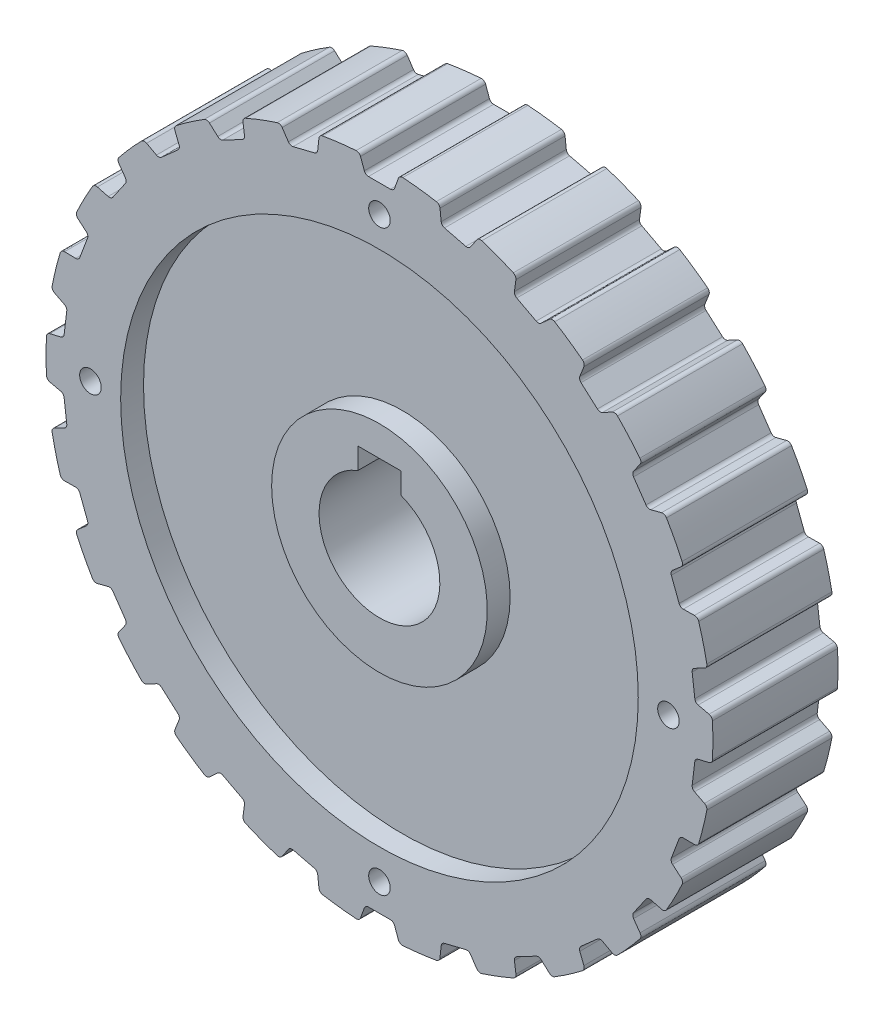
SolidWorks part; units mm, degrees
ref_plane "Front Plane" through (0, 0, 0) normal (0, 0, 1) x (1, 0, 0)
ref_plane "Top Plane" through (0, 0, 0) normal (0, 1, 0) x (1, 0, 0)
ref_plane "Right Plane" through (0, 0, 0) normal (1, 0, 0) x (0, 0, -1)
sketch "Sketch1" plane through (0, 0, 0) normal (0, 1, 0) x (1, 0, 0)
  line L0 (0, 36.1296) -> (0, -19.4741) construction
sketch "Sketch2" plane through (0, 0, 0) normal (0, 1, 0) x (1, 0, 0)
  line L0 (7, 7.25) -> (12.5, 7.25)
  line L1 (12.5, 7.25) -> (12.5, 4)
  line L2 (12.5, 4) -> (30, 4)
  line L3 (30, 4) -> (30, 7.25)
  line L4 (30, 7.25) -> (36, 7.25)
  line L5 (36, 7.25) -> (36, -7.25)
  line L6 (36, -7.25) -> (30, -7.25)
  line L7 (30, -7.25) -> (30, -4)
  line L8 (30, -4) -> (12.5, -4)
  line L9 (12.5, -4) -> (12.5, -7.25)
  line L10 (12.5, -7.25) -> (7, -7.25)
  line L11 (7, -7.25) -> (7, 7.25)
  line L12 (0, 0) -> (7, 0) construction
  line L13 (0, 200036.1296) -> (0, -200019.4741) construction
  dimension "D1" = 36
  dimension "D2" = 30
  dimension "D3" = 12.5
  dimension "D4" = 14.5
  dimension "D5" = 3.25
  dimension "D6" = 7
revolve "Revolve1" add sketch "Sketch2" angle 360 about L0
sketch "Sketch3" plane through (0, 0, 0) normal (0, 0, 1) x (1, 0, 0)
  line L0 (0, 0) -> (0, 9) construction
  line L1 (-2.5, 0) -> (2.5, 0)
  line L2 (-2.5, 0) -> (-2.5, 9)
  line L3 (-2.5, 9) -> (2.5, 9)
  line L4 (2.5, 0) -> (2.5, 9)
  line L5 (0, 9) -> (0, 12.5) construction
  circle A0 centre (0, 0) radius 12.5 construction
  dimension "D1" = 3.5
  dimension "D2" = 5
extrude "Cut-Extrude1" cut sketch "Sketch3" against normal through all both and the other way through all
sketch "Sketch4" plane through (0, 0, 0) normal (0, 0, 1) x (1, 0, 0)
  line L0 (0, 0) -> (0, 30) construction
  line L1 (0, 30) -> (0, 32) construction
  line L2 (0, 32) -> (0, 33.5) construction
  circle A0 centre (0, 0) radius 30 construction
  circle A1 centre (0, 33.5) radius 1.5 construction
  circle A2 centre (33.5, 0) radius 1.5 construction
  circle A3 centre (0, -33.5) radius 1.5 construction
  circle A4 centre (-33.5, 0) radius 1.5 construction
  point P18 (0, 0)
  dimension "D2" = 3
  dimension "D1" = 2
  dimension "D3" = 4
hole_wizard "M3x0.5 Tapped Hole1" positions "Sketch5" profile "Sketch6" tap size "M3x0.5" standard "ANSI Metric" end condition through all
sketch "Sketch5" plane through (0, 0, 7.25) normal (0, 0, 1) x (1, 0, 0)
  point P0 (0, 33.5)
  point P3 (33.5, 0)
  point P6 (-33.5, 0)
  point P9 (0, -33.5)
sketch "Sketch6" plane through (0, 33.5, 7.25) normal (1, 0, 0) x (0, -1, 0)
  line L0 (0, 0) -> (0, 14.5)
  line L1 (0, 14.5) -> (1.25, 14.5)
  line L2 (1.25, 14.5) -> (1.25, 0)
  line L5 (1.25, 0) -> (0, 0)
  line L11 (0, -6.35) -> (0, 107.95) construction
  dimension "Thru Tap Drill Dia." = 2.5
  dimension "Thru Tap Drill Depth" = 14.5
cosmetic thread "Hole Thread1" parameters "D2"=3
cosmetic thread "Hole Thread2" parameters "D2"=3
cosmetic thread "Hole Thread3" parameters "D2"=3
cosmetic thread "Hole Thread4" parameters "D2"=3
sketch "Sketch7" plane through (0, 0, 0) normal (0, 0, 1) x (1, 0, 0)
  line L0 (0, 0) -> (0, 37.6222) construction
  line L1 (-2.325, 38.5772) -> (-2.9401, 40.2672) construction
  line L2 (-2.325, 38.5772) -> (-1.6298, 36.6672) construction
  line L3 (-1.6298, 36.6672) -> (1.6298, 36.6672) construction
  line L4 (1.6298, 36.6672) -> (2.325, 38.5772) construction
  line L5 (2.325, 38.5772) -> (-2.325, 38.5772) construction
  line L6 (0, 36.6672) -> (0, 38.5772) construction
  line L7 (-2.9401, 40.2672) -> (2.9401, 40.2672) construction
  line L8 (2.9401, 40.2672) -> (2.325, 38.5772) construction
  line L9 (0, 38.5772) -> (0, 38.6472) construction
  line L10 (0, 38.6472) -> (0, 40.3744) construction
  line L11 (0, 0) -> (9.0036, 36.529) construction
  line L12 (9.0036, 36.529) -> (9.2489, 37.5242) construction
  line L13 (9.2489, 37.5242) -> (9.6622, 39.2012) construction
  line L14 (0, 39.5108) -> (9.4556, 38.3627) construction
  circle A0 centre (0, 0) radius 36
  circle A1 centre (0, 0) radius 37.6222 construction
  circle A2 centre (-1.2727, 37.1772) radius 0.51 construction
  circle A3 centre (1.2727, 37.1772) radius 0.51 construction
  circle A4 centre (0, 0) radius 38.6472
  circle A5 centre (0, 0) radius 36 construction
  circle A6 centre (0, 0) radius 40.3744 construction
  dimension "D3" = 40
  dimension "D6" = 1.02
  dimension "D1" = 3.6
  dimension "D2" = 9.525
  dimension "D7" = 13.846
  dimension "D4" = 1.91
  dimension "D5" = 4.65
extrude "Boss-Extrude1" add sketch "Sketch7" along normal up to surface and the other way up to surface up to face at (1.25, 33.5, 7.25) other way up to face at (1.25, 33.5, -7.25)
sketch "Sketch8" plane through (0, 0, 0) normal (0, 0, 1) x (1, 0, 0)
  line L6 (-1.6298, 36.6672) -> (-2.3505, 38.6472)
  line L7 (-2.3505, 38.6472) -> (2.3505, 38.6472)
  line L8 (2.3505, 38.6472) -> (1.6298, 36.6672)
  line L9 (1.6298, 36.6672) -> (-1.6298, 36.6672)
  line L10 (-2.325, 38.5772) -> (-1.6298, 36.6672) construction
  line L11 (1.6298, 36.6672) -> (2.325, 38.5772) construction
  line L12 (7.1926, 35.9918) -> (6.9667, 38.0867)
  line L13 (6.9667, 38.0867) -> (11.5311, 36.9617)
  line L14 (11.5311, 36.9617) -> (10.3575, 35.2117)
  line L15 (10.3575, 35.2117) -> (7.1926, 35.9918)
  line L16 (15.597, 33.2246) -> (15.879, 35.3127)
  line L17 (15.879, 35.3127) -> (20.0415, 33.1281)
  line L18 (20.0415, 33.1281) -> (18.4832, 31.7098)
  line L19 (18.4832, 31.7098) -> (15.597, 33.2246)
  line L20 (23.0949, 28.5266) -> (23.8685, 30.4865)
  line L21 (23.8685, 30.4865) -> (27.3872, 27.3692)
  line L22 (27.3872, 27.3692) -> (25.5348, 26.365)
  line L23 (25.5348, 26.365) -> (23.0949, 28.5266)
  line L24 (29.2507, 22.1707) -> (30.4708, 23.8885)
  line L25 (30.4708, 23.8885) -> (33.1412, 20.0197)
  line L26 (33.1412, 20.0197) -> (31.1024, 19.488)
  line L27 (31.1024, 19.488) -> (29.2507, 22.1707)
  line L28 (33.7065, 14.5263) -> (35.3023, 15.9022)
  line L29 (35.3023, 15.9022) -> (36.9692, 11.5068)
  line L30 (36.9692, 11.5068) -> (34.8624, 11.4785)
  line L31 (34.8624, 11.4785) -> (33.7065, 14.5263)
  line L32 (36.2034, 6.0377) -> (38.0821, 6.9917)
  line L33 (38.0821, 6.9917) -> (38.6487, 2.3251)
  line L34 (38.6487, 2.3251) -> (36.5963, 2.8018)
  line L35 (36.5963, 2.8018) -> (36.2034, 6.0377)
  line L36 (36.5963, -2.8018) -> (38.6487, -2.3251)
  line L37 (38.6487, -2.3251) -> (38.0821, -6.9917)
  line L38 (38.0821, -6.9917) -> (36.2034, -6.0377)
  line L39 (36.2034, -6.0377) -> (36.5963, -2.8018)
  line L40 (34.8624, -11.4785) -> (36.9692, -11.5068)
  line L41 (36.9692, -11.5068) -> (35.3023, -15.9022)
  line L42 (35.3023, -15.9022) -> (33.7065, -14.5263)
  line L43 (33.7065, -14.5263) -> (34.8624, -11.4785)
  line L44 (31.1024, -19.488) -> (33.1412, -20.0197)
  line L45 (33.1412, -20.0197) -> (30.4708, -23.8885)
  line L46 (30.4708, -23.8885) -> (29.2507, -22.1707)
  line L47 (29.2507, -22.1707) -> (31.1024, -19.488)
  line L48 (25.5348, -26.365) -> (27.3872, -27.3692)
  line L49 (27.3872, -27.3692) -> (23.8685, -30.4865)
  line L50 (23.8685, -30.4865) -> (23.0949, -28.5266)
  line L51 (23.0949, -28.5266) -> (25.5348, -26.365)
  line L52 (18.4832, -31.7098) -> (20.0415, -33.1281)
  line L53 (20.0415, -33.1281) -> (15.879, -35.3127)
  line L54 (15.879, -35.3127) -> (15.597, -33.2246)
  line L55 (15.597, -33.2246) -> (18.4832, -31.7098)
  line L56 (10.3575, -35.2117) -> (11.5311, -36.9617)
  line L57 (11.5311, -36.9617) -> (6.9667, -38.0867)
  line L58 (6.9667, -38.0867) -> (7.1926, -35.9918)
  line L59 (7.1926, -35.9918) -> (10.3575, -35.2117)
  line L60 (1.6298, -36.6672) -> (2.3505, -38.6472)
  line L61 (2.3505, -38.6472) -> (-2.3505, -38.6472)
  line L62 (-2.3505, -38.6472) -> (-1.6298, -36.6672)
  line L63 (-1.6298, -36.6672) -> (1.6298, -36.6672)
  line L64 (-7.1926, -35.9918) -> (-6.9667, -38.0867)
  line L65 (-6.9667, -38.0867) -> (-11.5311, -36.9617)
  line L66 (-11.5311, -36.9617) -> (-10.3575, -35.2117)
  line L67 (-10.3575, -35.2117) -> (-7.1926, -35.9918)
  line L68 (-15.597, -33.2246) -> (-15.879, -35.3127)
  line L69 (-15.879, -35.3127) -> (-20.0415, -33.1281)
  line L70 (-20.0415, -33.1281) -> (-18.4832, -31.7098)
  line L71 (-18.4832, -31.7098) -> (-15.597, -33.2246)
  line L72 (-23.0949, -28.5266) -> (-23.8685, -30.4865)
  line L73 (-23.8685, -30.4865) -> (-27.3872, -27.3692)
  line L74 (-27.3872, -27.3692) -> (-25.5348, -26.365)
  line L75 (-25.5348, -26.365) -> (-23.0949, -28.5266)
  line L76 (-29.2507, -22.1707) -> (-30.4708, -23.8885)
  line L77 (-30.4708, -23.8885) -> (-33.1412, -20.0197)
  line L78 (-33.1412, -20.0197) -> (-31.1024, -19.488)
  line L79 (-31.1024, -19.488) -> (-29.2507, -22.1707)
  line L80 (-33.7065, -14.5263) -> (-35.3023, -15.9022)
  line L81 (-35.3023, -15.9022) -> (-36.9692, -11.5068)
  line L82 (-36.9692, -11.5068) -> (-34.8624, -11.4785)
  line L83 (-34.8624, -11.4785) -> (-33.7065, -14.5263)
  line L84 (-36.2034, -6.0377) -> (-38.0821, -6.9917)
  line L85 (-38.0821, -6.9917) -> (-38.6487, -2.3251)
  line L86 (-38.6487, -2.3251) -> (-36.5963, -2.8018)
  line L87 (-36.5963, -2.8018) -> (-36.2034, -6.0377)
  line L88 (-36.5963, 2.8018) -> (-38.6487, 2.3251)
  line L89 (-38.6487, 2.3251) -> (-38.0821, 6.9917)
  line L90 (-38.0821, 6.9917) -> (-36.2034, 6.0377)
  line L91 (-36.2034, 6.0377) -> (-36.5963, 2.8018)
  line L92 (-34.8624, 11.4785) -> (-36.9692, 11.5068)
  line L93 (-36.9692, 11.5068) -> (-35.3023, 15.9022)
  line L94 (-35.3023, 15.9022) -> (-33.7065, 14.5263)
  line L95 (-33.7065, 14.5263) -> (-34.8624, 11.4785)
  line L96 (-31.1024, 19.488) -> (-33.1412, 20.0197)
  line L97 (-33.1412, 20.0197) -> (-30.4708, 23.8885)
  line L98 (-30.4708, 23.8885) -> (-29.2507, 22.1707)
  line L99 (-29.2507, 22.1707) -> (-31.1024, 19.488)
  line L100 (-25.5348, 26.365) -> (-27.3872, 27.3692)
  line L101 (-27.3872, 27.3692) -> (-23.8685, 30.4865)
  line L102 (-23.8685, 30.4865) -> (-23.0949, 28.5266)
  line L103 (-23.0949, 28.5266) -> (-25.5348, 26.365)
  line L104 (-18.4832, 31.7098) -> (-20.0415, 33.1281)
  line L105 (-20.0415, 33.1281) -> (-15.879, 35.3127)
  line L106 (-15.879, 35.3127) -> (-15.597, 33.2246)
  line L107 (-15.597, 33.2246) -> (-18.4832, 31.7098)
  line L108 (-10.3575, 35.2117) -> (-11.5311, 36.9617)
  line L109 (-11.5311, 36.9617) -> (-6.9667, 38.0867)
  line L110 (-6.9667, 38.0867) -> (-7.1926, 35.9918)
  line L111 (-7.1926, 35.9918) -> (-10.3575, 35.2117)
  circle A0 centre (0, 0) radius 38.6472 construction
  point P119 (0, 0)
  dimension "D1" = 26
extrude "Cut-Extrude2" cut sketch "Sketch8" against normal through all both and the other way through all
fillet "Fillet2" radius 0.51 104 edges at (-6.9747, 38.0126, 0) (-11.4896, 36.8998, 0) (-15.869, 35.2389, 0) (-19.9864, 33.0779, 0) (-23.8411, 30.4172, 0) (-27.3217, 27.3337, 0) (-30.4277, 23.8278, 0) (-33.0692, 20.0009, 0) (-35.2459, 15.8536, 0) (-36.8948, 11.5058, 0) (-38.0157, 6.958, 0) (-38.5762, 2.3419, 0) (-38.5762, -2.3419, 0) (-38.0157, -6.958, 0) (-36.8948, -11.5058, 0) (-35.2459, -15.8536, 0) (-33.0692, -20.0009, 0) (-30.4277, -23.8278, 0) (-27.3217, -27.3337, 0) (-23.8411, -30.4172, 0) (-19.9864, -33.0779, 0) (-15.869, -35.2389, 0) (-11.4896, -36.8998, 0) (-6.9747, -38.0126, 0) (-2.325, -38.5772, 0) (2.325, -38.5772, 0) (6.9747, -38.0126, 0) (11.4896, -36.8998, 0) (15.869, -35.2389, 0) (19.9864, -33.0779, 0) (23.8411, -30.4172, 0) (27.3217, -27.3337, 0) (30.4277, -23.8278, 0) (33.0692, -20.0009, 0) (35.2459, -15.8536, 0) (36.8948, -11.5058, 0) (38.0157, -6.958, 0) (38.5762, -2.3419, 0) (38.5762, 2.3419, 0) (38.0157, 6.958, 0) (36.8948, 11.5058, 0) (35.2459, 15.8536, 0) (33.0692, 20.0009, 0) (30.4277, 23.8278, 0) (27.3217, 27.3337, 0) (23.8411, 30.4172, 0) (19.9864, 33.0779, 0) (15.869, 35.2389, 0) (11.4896, 36.8998, 0) (6.9747, 38.0126, 0) (2.325, 38.5772, 0) (-7.1926, 35.9918, 0) (-10.3575, 35.2117, 0) (-15.597, 33.2246, 0) (-18.4832, 31.7098, 0) (-23.0949, 28.5266, 0) (-25.5348, 26.365, 0) (-29.2507, 22.1707, 0) (-31.1024, 19.488, 0) (-33.7065, 14.5263, 0) (-34.8624, 11.4785, 0) (-36.2034, 6.0377, 0) (-36.5963, 2.8018, 0) (-36.5963, -2.8018, 0) (-36.2034, -6.0377, 0) (-34.8624, -11.4785, 0) (-33.7065, -14.5263, 0) (-31.1024, -19.488, 0) (-29.2507, -22.1707, 0) (-25.5348, -26.365, 0) (-23.0949, -28.5266, 0) (-18.4832, -31.7098, 0) (-15.597, -33.2246, 0) (-10.3575, -35.2117, 0) (-7.1926, -35.9918, 0) (-1.6298, -36.6672, 0) (1.6298, -36.6672, 0) (7.1926, -35.9918, 0) (10.3575, -35.2117, 0) (15.597, -33.2246, 0) (18.4832, -31.7098, 0) (23.0949, -28.5266, 0) (25.5348, -26.365, 0) (29.2507, -22.1707, 0) (31.1024, -19.488, 0) (33.7065, -14.5263, 0) (34.8624, -11.4785, 0) (36.2034, -6.0377, 0) (36.5963, -2.8018, 0) (36.5963, 2.8018, 0) (36.2034, 6.0377, 0) (34.8624, 11.4785, 0) (33.7065, 14.5263, 0) (31.1024, 19.488, 0) (29.2507, 22.1707, 0) (25.5348, 26.365, 0) (23.0949, 28.5266, 0) (18.4832, 31.7098, 0) (15.597, 33.2246, 0) (10.3575, 35.2117, 0) (7.1926, 35.9918, 0) (1.6298, 36.6672, 0) (-1.6298, 36.6672, 0) (-2.325, 38.5772, 0)
sketch "Sketch9" plane through (0, 0, 4) normal (0, 0, 1) x (1, 0, 0)
  circle A0 centre (0, 0) radius 30
  circle A1 centre (0, 0) radius 12.5
  circle A2 centre (0, 0) radius 12.5 construction
  circle A3 centre (0, 0) radius 30 construction
extrude "Boss-Extrude2" add sketch "Sketch9" along normal blind 0.6
